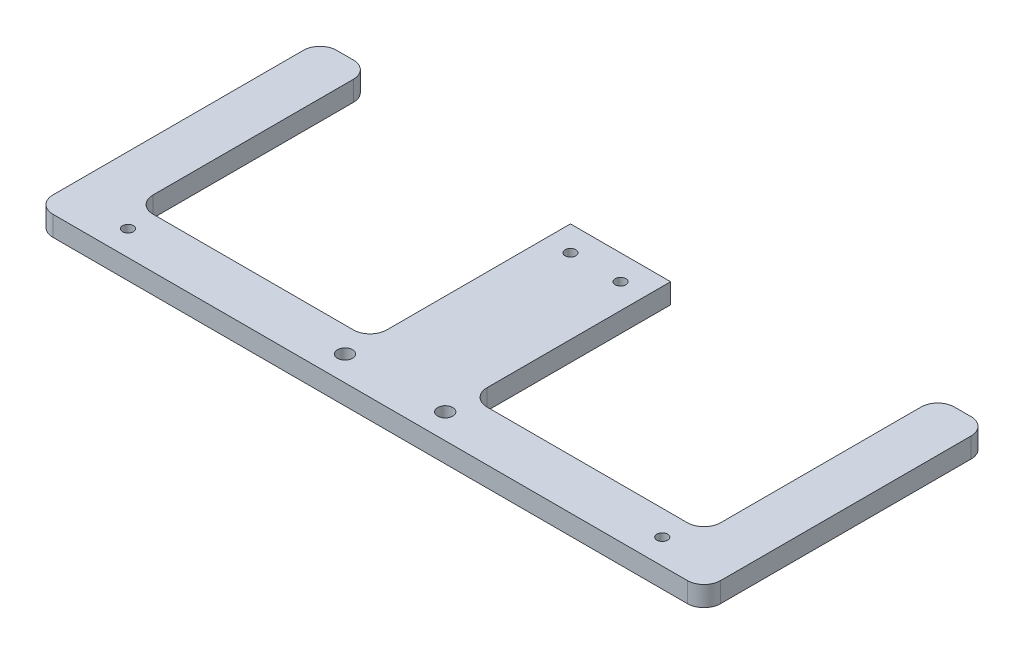
SolidWorks part; units mm, degrees
ref_plane "Front Plane" through (0, 0, 0) normal (0, 0, 1) x (1, 0, 0)
ref_plane "Top Plane" through (0, 0, 0) normal (0, 1, 0) x (1, 0, 0)
ref_plane "Right Plane" through (0, 0, 0) normal (1, 0, 0) x (0, 0, -1)
sketch "Sketch1" plane through (0, 0, 0) normal (0, 1, 0) x (1, 0, 0)
  line L1 (-85, 0) -> (-85, 70)
  line L2 (-85, 70) -> (-100, 70)
  line L3 (-100, 70) -> (-100, -15)
  line L4 (-100, -15) -> (0, -15)
  line L5 (0, -15) -> (0, 0)
  line L6 (-15, 0) -> (-15, 60)
  line L7 (-15, 60) -> (0, 60)
  line L8 (0, 60) -> (0, 0)
  line L9 (-85, 0) -> (-15, 0)
  dimension "D1" = 100
  dimension "D2" = 70
  dimension "D3" = 15
  dimension "D4" = 15
  dimension "D5" = 60
extrude "Boss-Extrude1" add sketch "Sketch1" along normal blind 6
fillet "Fillet1" radius 5 5 edges at (-100, 3, 15) (-100, 3, -70) (-85, 3, -70) (-15, 3, 0) (-85, 3, 0)
sketch "Sketch2" plane through (0, 6, 0) normal (0, 1, 0) x (1, 0, 0)
  line L0 (-15, 0) -> (-15, -15) construction
  line L1 (0, 60) -> (-15, 60) construction
  line L2 (-95, -15) -> (0, -15) construction
  line L3 (-15, 52.5) -> (0, 52.5) construction
  line L4 (-15, 60) -> (-15, 5) construction
  line L5 (0, -15) -> (0, 60) construction
  line L6 (0, 52.5) -> (-7.5, 52.5) construction
  circle A0 centre (-15, -7.5) radius 2.25
  circle A1 centre (-80, -7.5) radius 1.6
  circle A2 centre (-7.5, 52.5) radius 1.6
  point P13 (-7.0753, 52.901)
  dimension "D1" = 4.5
  dimension "D3" = 3.2
  dimension "D2" = 15
  dimension "D4" = 7.5
extrude "Cut-Extrude1" cut sketch "Sketch2" against normal through all
mirror "Mirror1" about plane through (0, 0, 0) normal (1, 0, 0) of "Cut-Extrude1", "Boss-Extrude1", "Fillet1"
